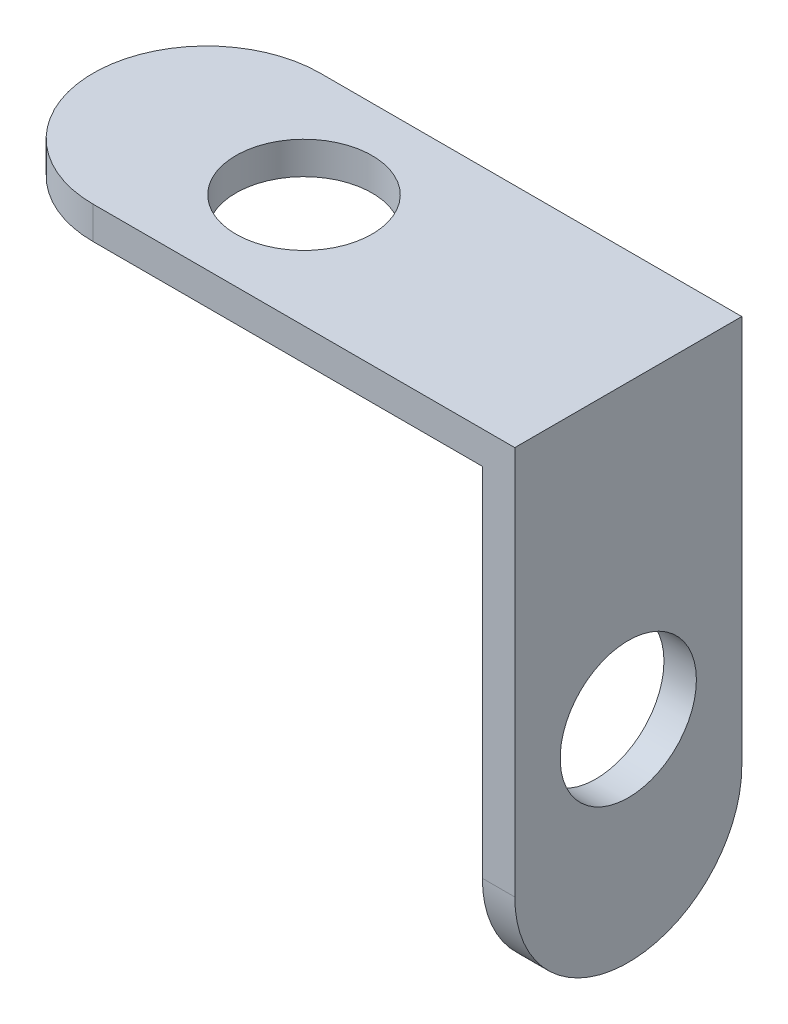
SolidWorks part; units mm, degrees
ref_plane "Спереди" through (0, 0, 0) normal (0, 0, 1) x (1, 0, 0)
ref_plane "Сверху" through (0, 0, 0) normal (0, 1, 0) x (1, 0, 0)
ref_plane "Справа" through (0, 0, 0) normal (1, 0, 0) x (0, 0, -1)
sketch "Эскиз1" plane through (0, 0, 0) normal (0, 1, 0) x (1, 0, 0)
  line L0 (0, -7) -> (-7, -7)
  line L5 (0, 0) -> (-7, 0)
  line L7 (0, 0) -> (5, 0)
  line L9 (0, -7) -> (5, -7)
  line L10 (5, 0) -> (5, -7)
  circle A0 centre (-4, -3.5) radius 2.1
  arc A2 (-7, 0) -> (-7, -7) centre (-7, -3.5) ccw
extrude "Бобышка-Вытянуть1" add sketch "Эскиз1" along normal blind 1 contours A0 | L0 A2 L5 L7 L10 L9
sketch "Эскиз2" plane through (5, 0, 0) normal (1, 0, 0) x (0, 0, -1)
  line L8 (0, -11) -> (0, 1)
  line L9 (0, 1) -> (0, 0) construction
  line L10 (0, 1) -> (-7, 1)
  line L11 (-7, -11) -> (-7, 1)
  circle A0 centre (-3.5, -8) radius 2.1
  arc A1 (-7, -11) -> (0, -11) centre (-3.5, -11) ccw
extrude "Бобышка-Вытянуть2" add sketch "Эскиз2" along normal blind 1
scale "Масштаб2" scale about centroid uniform scaling yes scale factor 0.5
scale "Масштаб1" scale about centroid uniform scaling yes scale factor 0.5
scale "Масштаб3" scale about centroid uniform scaling yes scale factor 2
